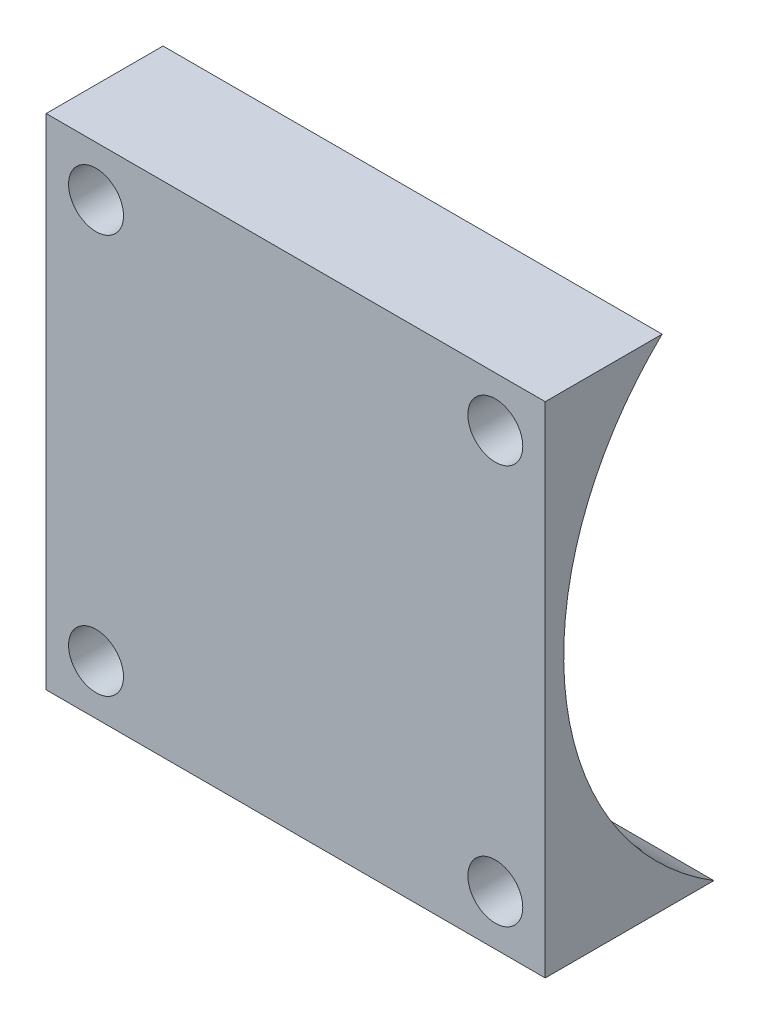
SolidWorks part; units mm, degrees
ref_plane "Front Plane" through (0, 0, 0) normal (0, 0, 1) x (1, 0, 0)
ref_plane "Top Plane" through (0, 0, 0) normal (0, 1, 0) x (1, 0, 0)
ref_plane "Right Plane" through (0, 0, 0) normal (1, 0, 0) x (0, 0, -1)
sketch "Sketch1" plane through (0, 0, 0) normal (0, 0, 1) x (1, 0, 0)
  line L1 (-25, 23) -> (25, 23)
  line L2 (-25, 23) -> (-25, -27)
  line L3 (-25, -27) -> (25, -27)
  line L4 (25, 23) -> (25, -27)
  line L5 (-25, 23) -> (25, -27) construction
  line L6 (-25, -27) -> (25, 23) construction
  circle A1 centre (-20, 18) radius 2.75
  circle A2 centre (20, 18) radius 2.75
  circle A3 centre (20, -22) radius 2.75
  circle A4 centre (-20, -22) radius 2.75
  point P0 (0, -2)
  dimension "D6" = 5.5
  dimension "D1" = 2
  dimension "D2" = 50
  dimension "D3" = 50
  dimension "D5" = 20
  dimension "D7" = 20
  dimension "D9" = 20
  dimension "D10" = 20
extrude "Boss-Extrude1" add sketch "Sketch1" along normal blind 33.6
sketch "Sketch2" plane through (0, 0, 0) normal (1, 0, 0) x (0, 0, -1)
  circle A0 centre (0, 0) radius 31.75
  dimension "D1" = 63.5
extrude "Cut-Extrude1" cut sketch "Sketch2" against normal through all and the other way through all
